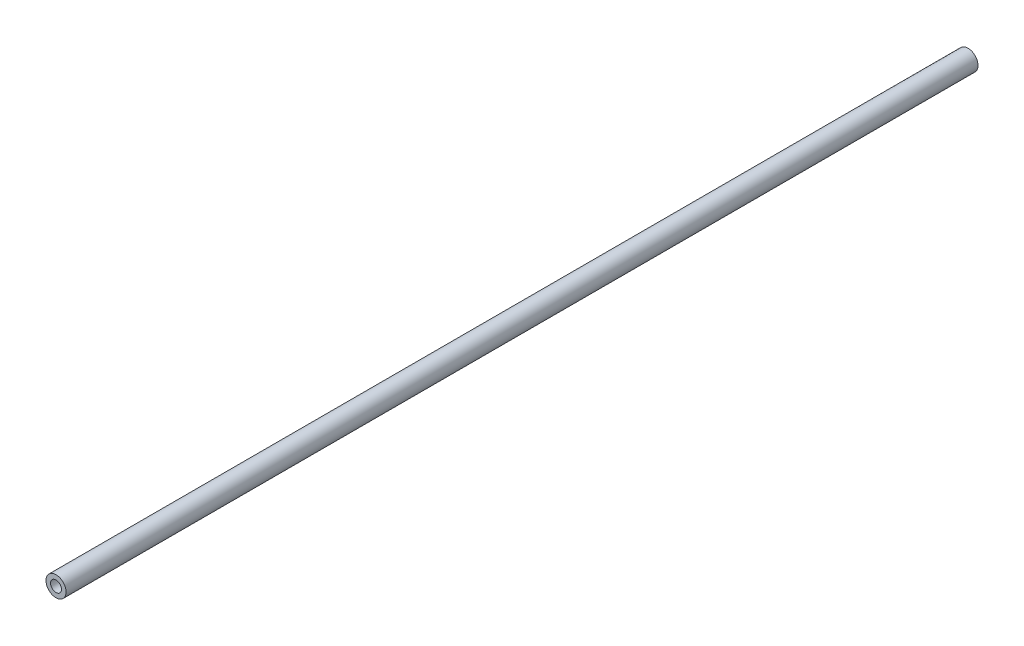
SolidWorks part; units mm, degrees
material "PVC Rigid"
ref_plane "Front Plane" through (0, 0, 0) normal (0, 0, 1) x (1, 0, 0)
ref_plane "Top Plane" through (0, 0, 0) normal (0, 1, 0) x (1, 0, 0)
ref_plane "Right Plane" through (0, 0, 0) normal (1, 0, 0) x (0, 0, -1)
sketch "Sketch1" plane through (0, 0, 0) normal (0, 0, 1) x (1, 0, 0)
  circle A0 centre (0, 0) radius 11
  circle A2 centre (0, 0) radius 6
  dimension "D1" = 22
  dimension "D2" = 5
extrude "Boss-Extrude1" add sketch "Sketch1" along normal blind 1000
sketch "Sketch2" plane through (0, 0, 0) normal (0, 0, -1) x (-1, 0, 0)
  line L0 (-21.0309, 0) -> (21.0309, 0) construction
  circle A1 centre (0, 0) radius 11
  circle A2 centre (0, 0) radius 11
  point P6 (0, 0)
  dimension "D1" = 0
equation "\"pipe_od\"=22"
equation "\"D1@Sketch1\"=\"pipe_od\""
